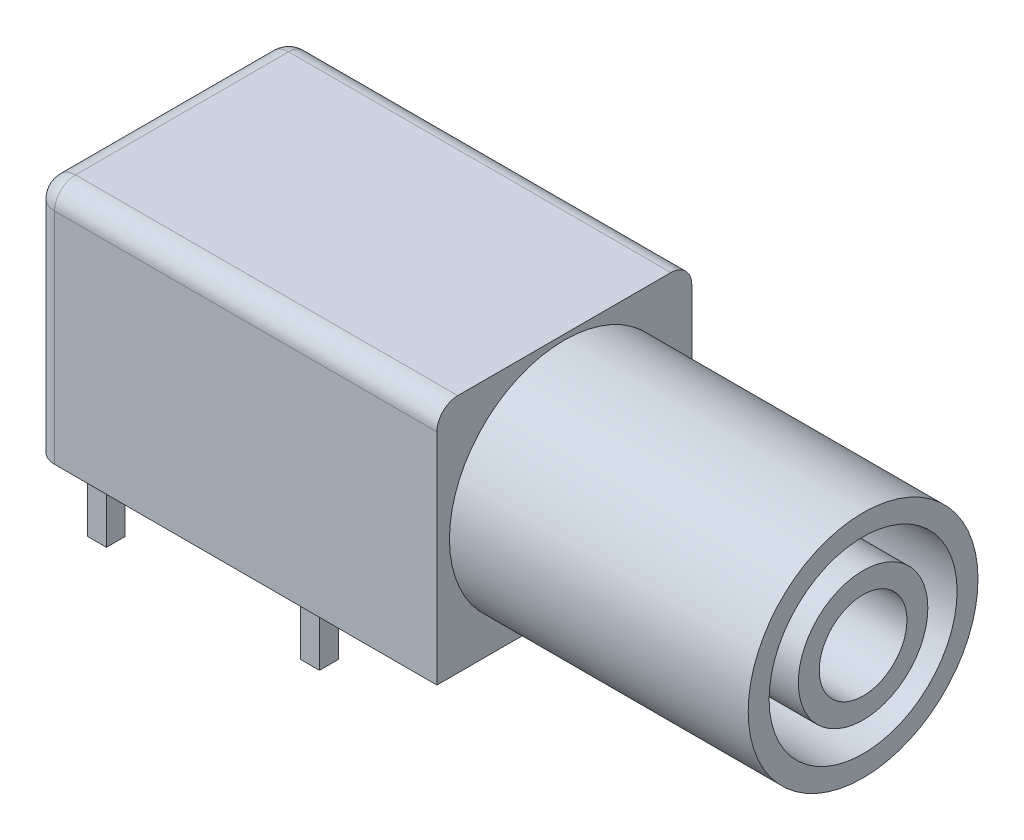
SolidWorks part; units mm, degrees
ref_plane "Спереди" through (0, 0, 0) normal (0, 0, 1) x (1, 0, 0)
ref_plane "Сверху" through (0, 0, 0) normal (0, 1, 0) x (1, 0, 0)
ref_plane "Справа" through (0, 0, 0) normal (1, 0, 0) x (0, 0, -1)
sketch "Эскиз1" plane through (0, 0, 0) normal (0, 1, 0) x (1, 0, 0)
  line L1 (-9.65, 6.1) -> (9.65, 6.1)
  line L2 (-9.65, 6.1) -> (-9.65, -6.1)
  line L3 (-9.65, -6.1) -> (9.65, -6.1)
  line L4 (9.65, 6.1) -> (9.65, -6.1)
  line L5 (-9.65, 6.1) -> (9.65, -6.1) construction
  line L6 (-9.65, -6.1) -> (9.65, 6.1) construction
  point P0 (0, 0)
  dimension "D1" = 19.3
  dimension "D2" = 12.2
extrude "Бобышка-Вытянуть1" add sketch "Эскиз1" along normal blind 11.5
fillet "Скругление4" radius 1 5 edges at (0, 11.5, -6.1) (0, 11.5, 6.1) (-9.65, 11.5, 0) (-9.65, 5.75, -6.1) (-9.65, 5.75, 6.1)
sketch "Эскиз2" plane through (9.65, 0, 0) normal (1, 0, 0) x (0, 0, -1)
  line L0 (-5.1, 11.5) -> (5.1, 11.5) construction
  line L1 (-6.1, 10.5) -> (-6.1, 0) construction
  circle A0 centre (0, 5.75) radius 5.5
  dimension "D3" = 11
  dimension "D1" = 5.75
  dimension "D2" = 6.1
extrude "Бобышка-Вытянуть2" add sketch "Эскиз2" along normal blind 14.3
sketch "Эскиз3" plane through (23.95, 0, 0) normal (1, 0, 0) x (0, 0, -1)
  circle A0 centre (0, 5.75) radius 4.5
  circle A1 centre (0, 5.75) radius 5.5 construction
  dimension "D1" = 9
extrude "Вырез-Вытянуть1" cut sketch "Эскиз3" against normal blind 14.3
sketch "Эскиз4" plane through (9.65, 0, 0) normal (1, 0, 0) x (0, 0, -1)
  circle A0 centre (0, 5.75) radius 3.1
  circle A1 centre (0, 5.75) radius 2.1
  dimension "D1" = 6.2
  dimension "D2" = 4.2
extrude "Бобышка-Вытянуть3" add sketch "Эскиз4" along normal blind 14.3
sketch "Эскиз5" plane through (0, 0, 0) normal (0, -1, 0) x (1, 0, 0)
  line L0 (-9.65, -5.1) -> (-9.65, 5.1) construction
  line L1 (-8.17, 5) -> (-6.67, 5)
  line L2 (-8.17, 5) -> (-8.17, 4.1)
  line L3 (-8.17, 4.1) -> (-6.67, 4.1)
  line L4 (-6.67, 5) -> (-6.67, 4.1)
  line L5 (-8.17, 5) -> (-6.67, 4.1) construction
  line L6 (-8.17, 4.1) -> (-6.67, 5) construction
  line L7 (-8.65, 6.1) -> (9.65, 6.1) construction
  point P0 (-7.42, 4.55)
  dimension "D1" = 1.48
  dimension "D2" = 1.1
  dimension "D3" = 1.5
  dimension "D4" = 0.9
extrude "Бобышка-Вытянуть4" add sketch "Эскиз5" along normal blind 0.9
sketch "Эскиз6" plane through (0, -0.9, 0) normal (0, -1, 0) x (1, 0, 0)
  line L0 (-8.17, 4.1) -> (-6.67, 4.1) construction
  line L1 (-8.17, 5) -> (-7.27, 5)
  line L2 (-8.17, 5) -> (-8.17, 4.1)
  line L3 (-8.17, 4.1) -> (-7.27, 4.1)
  line L4 (-7.27, 5) -> (-7.27, 4.1)
  dimension "D1" = 0.9
extrude "Бобышка-Вытянуть5" add sketch "Эскиз6" along normal blind 2.4
pattern_linear "Линейный массив1" count 2 spacing 9.1 along (0, 0, -1) of "Бобышка-Вытянуть5", "Бобышка-Вытянуть4"
ref_plane "Плоскость1" through (-2.62, 0, 0) normal (1, 0, 0) x (0, 0, -1)
mirror "Зеркальное отражение1" about plane through (-2.62, 0, 0) normal (1, 0, 0) of "Линейный массив1", "Бобышка-Вытянуть4", "Бобышка-Вытянуть5"
sketch "Эскиз7" plane through (0, 0, 0) normal (0, -1, 0) x (1, 0, 0)
  line L0 (-8.65, 6.1) -> (9.65, 6.1) construction
  line L1 (-9.65, -5.1) -> (-9.65, 5.1) construction
  circle A0 centre (-4.95, 0) radius 1
  point P6 (-4.5858, -0.7447)
  dimension "D1" = 2
  dimension "D2" = 6.1
  dimension "D3" = 4.7
extrude "Бобышка-Вытянуть6" add sketch "Эскиз7" along normal blind 3.3
